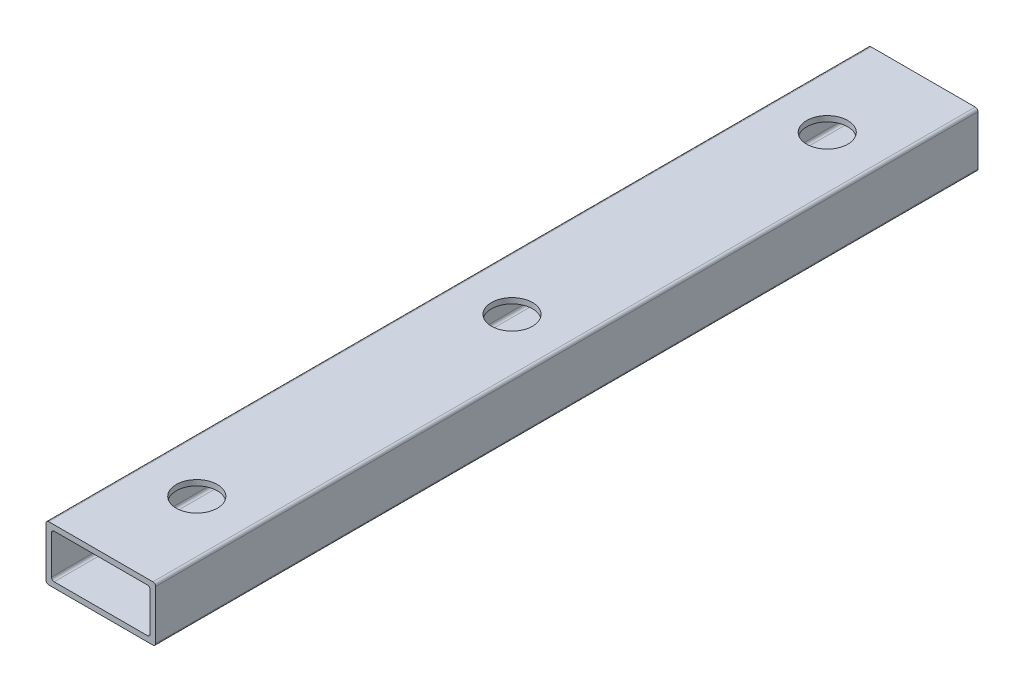
SolidWorks part; units mm, degrees
ref_plane "Plan de face" through (0, 0, 0) normal (0, 0, 1) x (1, 0, 0)
ref_plane "Plan de dessus" through (0, 0, 0) normal (0, 1, 0) x (1, 0, 0)
ref_plane "Plan de droite" through (0, 0, 0) normal (1, 0, 0) x (0, 0, -1)
sketch "Esquisse1" plane through (0, 0, 0) normal (0, 0, 1) x (1, 0, 0)
  line L0 (4, 4) -> (4, 32)
  line L1 (2, -2) -> (78, -2)
  line L2 (0, 0) -> (0, 36)
  line L3 (2, 38) -> (78, 38)
  line L4 (80, 0) -> (80, 36)
  line L5 (6, 34) -> (74, 34)
  line L6 (76, 4) -> (76, 32)
  line L7 (6, 2) -> (74, 2)
  line L8 (4, 2) -> (76, 2) construction
  line L9 (76, 2) -> (76, 34) construction
  line L10 (80, -2) -> (80, 38) construction
  line L11 (0, -2) -> (80, -2) construction
  line L12 (4, 34) -> (76, 34) construction
  line L13 (0, 38) -> (80, 38) construction
  line L14 (0, -2) -> (0, 38) construction
  line L15 (4, 2) -> (4, 34) construction
  arc A0 (74, 2) -> (76, 4) centre (74, 4) ccw
  arc A1 (80, 0) -> (78, -2) centre (78, 0) cw
  arc A2 (74, 34) -> (76, 32) centre (74, 32) cw
  arc A3 (80, 36) -> (78, 38) centre (78, 36) ccw
  arc A4 (0, 36) -> (2, 38) centre (2, 36) cw
  arc A5 (6, 34) -> (4, 32) centre (6, 32) ccw
  arc A6 (6, 2) -> (4, 4) centre (6, 4) cw
  arc A7 (0, 0) -> (2, -2) centre (2, 0) ccw
  dimension "D4" = 2
  dimension "D1" = 40
  dimension "D2" = 80
  dimension "D3" = 4
extrude "Boss.-Extru.1" add sketch "Esquisse1" along normal blind 600
sketch "Esquisse2" plane through (0, 38, 0) normal (0, 1, 0) x (1, 0, 0)
  line L0 (78, -300) -> (2, -300) construction
  line L1 (78, -600) -> (78, 0) construction
  line L2 (2, -600) -> (2, 0) construction
  line L3 (40, -300) -> (40, -70) construction
  circle A0 centre (40, -300) radius 15
  circle A1 centre (40, -70) radius 15
  circle A2 centre (40, -530) radius 15
  dimension "D1" = 30
  dimension "D2" = 30
  dimension "D3" = 230
extrude "Enlèv. mat.-Extru.1" cut sketch "Esquisse2" against normal through all
